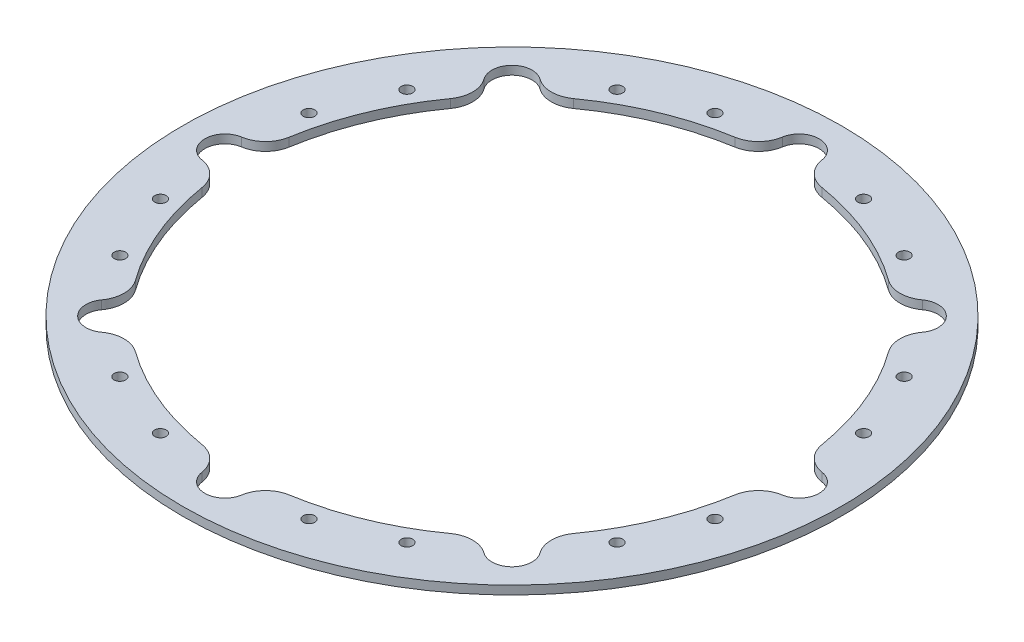
SolidWorks part; units mm, degrees
material "Thornel Mat VMA"
ref_plane "Front Plane" through (0, 0, 0) normal (0, 0, 1) x (1, 0, 0)
ref_plane "Top Plane" through (0, 0, 0) normal (0, 1, 0) x (1, 0, 0)
ref_plane "Right Plane" through (0, 0, 0) normal (1, 0, 0) x (0, 0, -1)
sketch "Sketch1" plane through (0, 0, 0) normal (0, 1, 0) x (1, 0, 0)
  line L0 (0, 0) -> (100.17, 0) construction
  line L1 (100.17, 0) -> (21.6753, 0) construction
  line L2 (100.17, -4) -> (21.6753, -4) construction
  line L3 (100.17, 4) -> (21.6753, 4) construction
  line L4 (70.8309, -70.8309) -> (15.3267, -15.3267) construction
  line L5 (68.0025, -73.6593) -> (12.4983, -18.1552) construction
  line L6 (73.6593, -68.0025) -> (18.1552, -12.4983) construction
  line L7 (0, -100.17) -> (0, -21.6753) construction
  line L8 (-4, -100.17) -> (-4, -21.6753) construction
  line L9 (4, -100.17) -> (4, -21.6753) construction
  line L10 (-70.8309, -70.8309) -> (-15.3267, -15.3267) construction
  line L11 (-73.6593, -68.0025) -> (-18.1552, -12.4983) construction
  line L12 (-68.0025, -73.6593) -> (-12.4983, -18.1552) construction
  line L13 (-100.17, 0) -> (-21.6753, 0) construction
  line L14 (-100.17, 4) -> (-21.6753, 4) construction
  line L15 (-100.17, -4) -> (-21.6753, -4) construction
  line L16 (-70.8309, 70.8309) -> (-15.3267, 15.3267) construction
  line L17 (-68.0025, 73.6593) -> (-12.4983, 18.1552) construction
  line L18 (-73.6593, 68.0025) -> (-18.1552, 12.4983) construction
  line L19 (0, 100.17) -> (0, 21.6753) construction
  line L20 (4, 100.17) -> (4, 21.6753) construction
  line L21 (-4, 100.17) -> (-4, 21.6753) construction
  line L22 (70.8309, 70.8309) -> (15.3267, 15.3267) construction
  line L23 (73.6593, 68.0025) -> (18.1552, 12.4983) construction
  line L24 (68.0025, 73.6593) -> (12.4983, 18.1552) construction
  line L25 (21.6753, 0) -> (100.17, 0) construction
  line L26 (21.6753, 7) -> (100.17, 7)
  line L27 (21.6753, -7) -> (100.17, -7)
  line L28 (15.3267, -15.3267) -> (70.8309, -70.8309) construction
  line L29 (20.2765, -10.377) -> (75.7806, -65.8811)
  line L30 (10.377, -20.2765) -> (65.8811, -75.7806)
  line L31 (0, -21.6753) -> (0, -100.17) construction
  line L32 (7, -21.6753) -> (7, -100.17)
  line L33 (-7, -21.6753) -> (-7, -100.17)
  line L34 (-15.3267, -15.3267) -> (-70.8309, -70.8309) construction
  line L35 (-10.377, -20.2765) -> (-65.8811, -75.7806)
  line L36 (-20.2765, -10.377) -> (-75.7806, -65.8811)
  line L37 (-21.6753, 0) -> (-100.17, 0) construction
  line L38 (-21.6753, -7) -> (-100.17, -7)
  line L39 (-21.6753, 7) -> (-100.17, 7)
  line L40 (-15.3267, 15.3267) -> (-70.8309, 70.8309) construction
  line L41 (-20.2765, 10.377) -> (-75.7806, 65.8811)
  line L42 (-10.377, 20.2765) -> (-65.8811, 75.7806)
  line L43 (0, 21.6753) -> (0, 100.17) construction
  line L44 (-7, 21.6753) -> (-7, 100.17)
  line L45 (7, 21.6753) -> (7, 100.17)
  line L46 (15.3267, 15.3267) -> (70.8309, 70.8309) construction
  line L47 (10.377, 20.2765) -> (65.8811, 75.7806)
  line L48 (20.2765, 10.377) -> (75.7806, 65.8811)
  circle A0 centre (0, 0) radius 94.17
  circle A1 centre (0, 0) radius 91.17 construction
  arc A2 (100.17, -4) -> (100.17, 4) centre (100.17, 0) ccw construction
  arc A3 (21.6753, 4) -> (21.6753, -4) centre (21.6753, 0) ccw construction
  arc A4 (68.0025, -73.6593) -> (73.6593, -68.0025) centre (70.8309, -70.8309) ccw construction
  arc A5 (18.1552, -12.4983) -> (12.4983, -18.1552) centre (15.3267, -15.3267) ccw construction
  arc A6 (-4, -100.17) -> (4, -100.17) centre (0, -100.17) ccw construction
  arc A7 (4, -21.6753) -> (-4, -21.6753) centre (0, -21.6753) ccw construction
  arc A8 (-73.6593, -68.0025) -> (-68.0025, -73.6593) centre (-70.8309, -70.8309) ccw construction
  arc A9 (-12.4983, -18.1552) -> (-18.1552, -12.4983) centre (-15.3267, -15.3267) ccw construction
  arc A10 (-100.17, 4) -> (-100.17, -4) centre (-100.17, 0) ccw construction
  arc A11 (-21.6753, -4) -> (-21.6753, 4) centre (-21.6753, 0) ccw construction
  arc A12 (-68.0025, 73.6593) -> (-73.6593, 68.0025) centre (-70.8309, 70.8309) ccw construction
  arc A13 (-18.1552, 12.4983) -> (-12.4983, 18.1552) centre (-15.3267, 15.3267) ccw construction
  arc A14 (4, 100.17) -> (-4, 100.17) centre (0, 100.17) ccw construction
  arc A15 (-4, 21.6753) -> (4, 21.6753) centre (0, 21.6753) ccw construction
  arc A16 (73.6593, 68.0025) -> (68.0025, 73.6593) centre (70.8309, 70.8309) ccw construction
  arc A17 (12.4983, 18.1552) -> (18.1552, 12.4983) centre (15.3267, 15.3267) ccw construction
  arc A18 (21.6753, 7) -> (21.6753, -7) centre (21.6753, 0) ccw
  arc A19 (100.17, -7) -> (100.17, 7) centre (100.17, 0) ccw
  arc A20 (20.2765, -10.377) -> (10.377, -20.2765) centre (15.3267, -15.3267) ccw
  arc A21 (65.8811, -75.7806) -> (75.7806, -65.8811) centre (70.8309, -70.8309) ccw
  arc A22 (7, -21.6753) -> (-7, -21.6753) centre (0, -21.6753) ccw
  arc A23 (-7, -100.17) -> (7, -100.17) centre (0, -100.17) ccw
  arc A24 (-10.377, -20.2765) -> (-20.2765, -10.377) centre (-15.3267, -15.3267) ccw
  arc A25 (-75.7806, -65.8811) -> (-65.8811, -75.7806) centre (-70.8309, -70.8309) ccw
  arc A26 (-21.6753, -7) -> (-21.6753, 7) centre (-21.6753, 0) ccw
  arc A27 (-100.17, 7) -> (-100.17, -7) centre (-100.17, 0) ccw
  arc A28 (-20.2765, 10.377) -> (-10.377, 20.2765) centre (-15.3267, 15.3267) ccw
  arc A29 (-65.8811, 75.7806) -> (-75.7806, 65.8811) centre (-70.8309, 70.8309) ccw
  arc A30 (-7, 21.6753) -> (7, 21.6753) centre (0, 21.6753) ccw
  arc A31 (7, 100.17) -> (-7, 100.17) centre (0, 100.17) ccw
  arc A32 (10.377, 20.2765) -> (20.2765, 10.377) centre (15.3267, 15.3267) ccw
  arc A33 (75.7806, 65.8811) -> (65.8811, 75.7806) centre (70.8309, 70.8309) ccw
  circle A34 centre (0, 0) radius 115
  point P6 (60.9226, 0)
  point P13 (60.9226, 0)
  point P16 (43.0788, -43.0788)
  point P23 (0, -60.9226)
  point P30 (-43.0788, -43.0788)
  point P37 (-60.9226, 0)
  point P44 (-43.0788, 43.0788)
  point P51 (0, 60.9226)
  point P58 (43.0788, 43.0788)
  point P63 (0, 0)
  point P69 (0, 0)
  point P72 (43.0788, -43.0788)
  point P79 (0, -60.9226)
  point P86 (-43.0788, -43.0788)
  point P93 (-60.9226, 0)
  point P100 (-43.0788, 43.0788)
  point P107 (0, 60.9226)
  point P114 (43.0788, 43.0788)
  point P119 (0, 0)
  point P120 (0, 0)
  point P121 (0, 100.17)
  dimension "D1" = 182.34
  dimension "D2" = 4
  dimension "D5" = 188.34
  dimension "D6" = 7
  dimension "D8" = 230
  dimension "D3" = 100.17
  dimension "D4" = 8
  dimension "D7" = 8
extrude "Boss-Extrude1" add sketch "Sketch1" along normal blind 3 contours A34 A33 L48 A0 L26 A19 L27 L29 A21 L30 L32 A23 L33 L35 A25 L36 L38 A27 L39 L41 A29 L42 L44 A31 L45 L47
sketch "Sketch2" plane through (0, 3, 0) normal (0, 1, 0) x (1, 0, 0)
  line L0 (100.17, 0) -> (0, 0) construction
  line L1 (0, 0) -> (96.7568, 25.9259) construction
  line L2 (86.7498, 50.085) -> (0, 0) construction
  circle A0 centre (0, 0) radius 100.17 construction
  circle A1 centre (96.7568, 25.9259) radius 2
  circle A2 centre (86.7498, -50.085) radius 2
  circle A3 centre (25.9259, -96.7568) radius 2
  circle A4 centre (-50.085, -86.7498) radius 2
  circle A5 centre (-96.7568, -25.9259) radius 2
  circle A6 centre (-86.7498, 50.085) radius 2
  circle A7 centre (-25.9259, 96.7568) radius 2
  circle A8 centre (50.085, 86.7498) radius 2
  circle A9 centre (86.7498, 50.085) radius 2
  circle A10 centre (96.7568, -25.9259) radius 2
  circle A11 centre (50.085, -86.7498) radius 2
  circle A12 centre (-25.9259, -96.7568) radius 2
  circle A13 centre (-86.7498, -50.085) radius 2
  circle A14 centre (-96.7568, 25.9259) radius 2
  circle A15 centre (-50.085, 86.7498) radius 2
  circle A16 centre (25.9259, 96.7568) radius 2
  point P23 (0, 0)
  point P40 (0, 0)
  dimension "D2" = 4
  dimension "D5" = 4
  dimension "D1" = 15
  dimension "D4" = 15
  dimension "D3" = 8
  dimension "D6" = 8
extrude "Cut-Extrude1" cut sketch "Sketch2" against normal blind 3
fillet "Fillet1" radius 10 16 edges at (-61.4543, 1.5, -71.3538) (-71.3538, 1.5, -61.4543) (-93.9095, 1.5, -7) (-93.9095, 1.5, 7) (-71.3538, 1.5, 61.4543) (-61.4543, 1.5, 71.3538) (-7, 1.5, 93.9095) (7, 1.5, 93.9095) (61.4543, 1.5, 71.3538) (71.3538, 1.5, 61.4543) (93.9095, 1.5, 7) (93.9095, 1.5, -7) (71.3538, 1.5, -61.4543) (61.4543, 1.5, -71.3538) (7, 1.5, -93.9095) (-7, 1.5, -93.9095)
